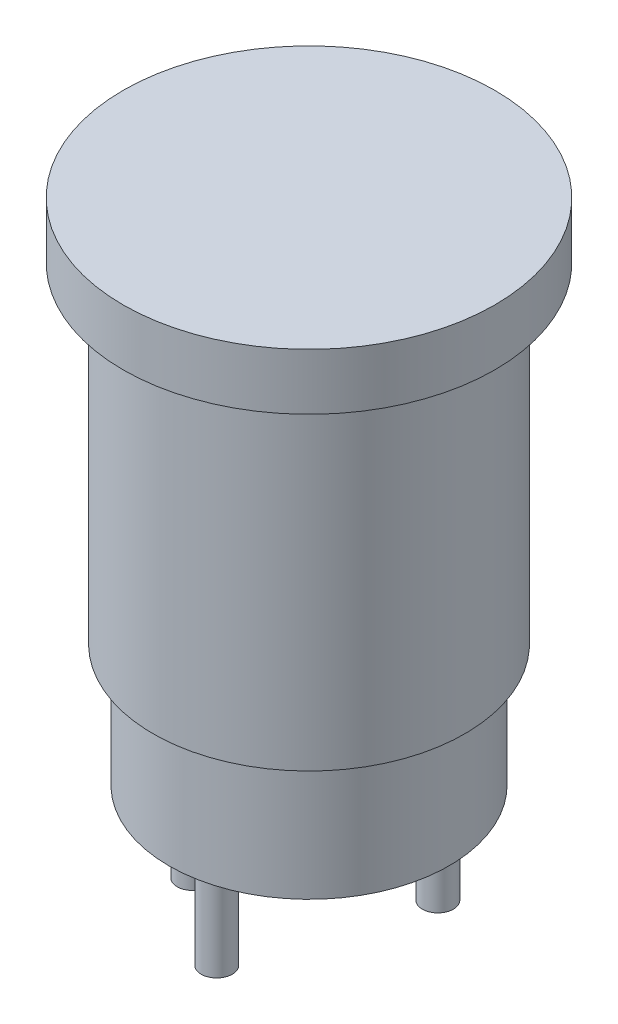
SolidWorks part; units mm, degrees
ref_plane "Front Plane" through (0, 0, 0) normal (0, 0, 1) x (1, 0, 0)
ref_plane "Top Plane" through (0, 0, 0) normal (0, 1, 0) x (1, 0, 0)
ref_plane "Right Plane" through (0, 0, 0) normal (1, 0, 0) x (0, 0, -1)
sketch "Sketch1" plane through (0, 0, 0) normal (0, 0, 1) x (1, 0, 0)
  line L0 (0, 0) -> (7.6, 0)
  line L1 (0, -55) -> (0, 55) construction
  line L2 (7.6, 0) -> (7.6, -2.3)
  line L3 (7.6, -2.3) -> (6.375, -2.3)
  line L4 (6.375, -2.3) -> (6.375, -15.8)
  line L5 (6.375, -15.8) -> (5.7284, -15.8)
  line L6 (5.7284, -15.8) -> (5.7284, -20.8)
  line L7 (5.7284, -20.8) -> (0, -20.8)
  line L8 (0, -20.8) -> (0, 0)
  dimension "D1" = 7.6
  dimension "D2" = 6.375
  dimension "D3" = 13.5
  dimension "D4" = 2.3
  dimension "D5" = 20.8
revolve "Revolve1" add sketch "Sketch1" angle 360 about L8
sketch "Sketch2" plane through (0, -20.8, 0) normal (0, -1, 0) x (1, 0, 0)
  circle A0 centre (0, 3.7731) radius 0.635
  dimension "D1" = 1.27
extrude "Boss-Extrude1" add sketch "Sketch2" along normal blind 4.5
pattern_circular "CirPattern1" count 4 every 72 about axis through (0, 0, 0) along (0, 1, 0) of "Boss-Extrude1"
